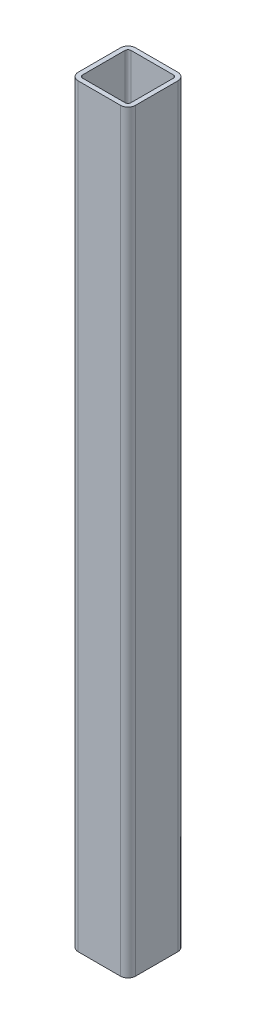
SolidWorks part; units mm, degrees
ref_plane "Front Plane" through (0, 0, 0) normal (0, 0, 1) x (1, 0, 0)
ref_plane "Top Plane" through (0, 0, 0) normal (0, 1, 0) x (1, 0, 0)
ref_plane "Right Plane" through (0, 0, 0) normal (1, 0, 0) x (0, 0, -1)
sketch "Sketch1" plane through (0, 0, 0) normal (0, 1, 0) x (1, 0, 0)
  line L1 (-19, -19) -> (19, -19)
  line L2 (-19, -19) -> (-19, 19)
  line L3 (-19, 19) -> (19, 19)
  line L4 (19, -19) -> (19, 19)
  line L5 (-19, -19) -> (19, 19) construction
  line L6 (-19, 19) -> (19, -19) construction
  point P0 (0, 0)
  dimension "D1" = 38
  dimension "D2" = 38
extrude "Boss-Extrude1" add sketch "Sketch1" along normal mid plane 500
fillet "Fillet1" radius 5 4 edges at (-19, 0, -19) (19, 0, -19) (19, 0, 19) (-19, 0, 19)
shell "Shell1" thickness 3
